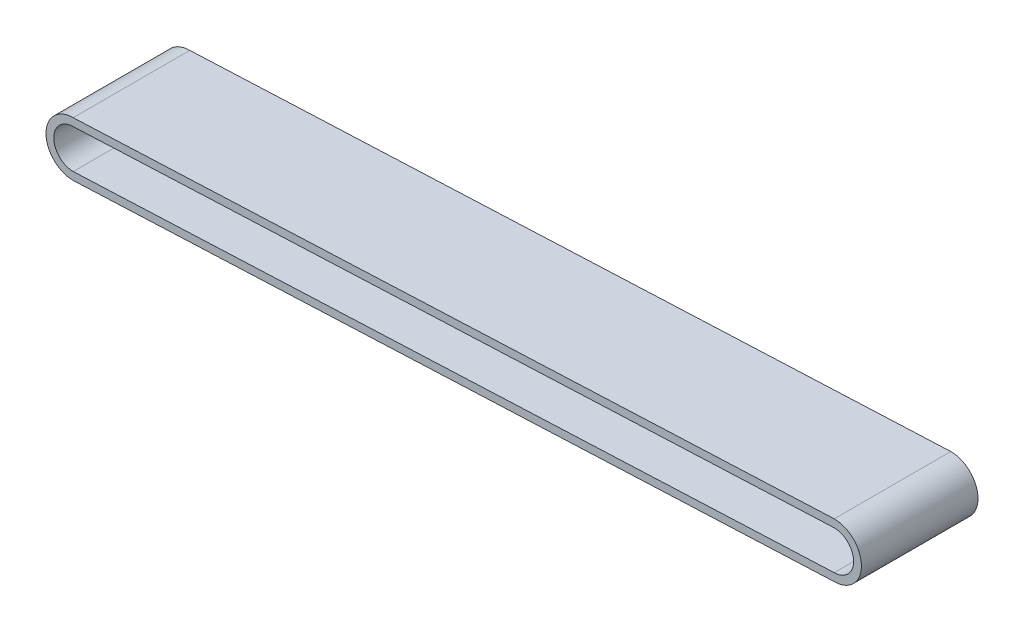
SolidWorks part; units mm, degrees
ref_plane "Front Plane" through (0, 0, 0) normal (0, 0, 1) x (1, 0, 0)
ref_plane "Top Plane" through (0, 0, 0) normal (0, 1, 0) x (1, 0, 0)
ref_plane "Right Plane" through (0, 0, 0) normal (1, 0, 0) x (0, 0, -1)
sketch "Sketch1" plane through (0, 0, 0) normal (0, 0, 1) x (1, 0, 0)
  line L1 (-230, -7.5) -> (259.5368, 13.8015)
  line L2 (-230, -32.5) -> (259.5368, -11.1985)
  line L3 (-207.5, -20) -> (-230, -20)
  line L4 (-230, -2.5) -> (259.5368, 18.8015)
  line L5 (-230, -37.5) -> (259.7542, -16.1972)
  arc A1 (-230, -7.5) -> (-230, -32.5) centre (-230, -20) ccw
  arc A2 (259.5368, -11.1985) -> (259.5368, 13.8015) centre (259.5368, 1.3015) ccw
  arc A3 (-230, -2.5) -> (-230, -37.5) centre (-230, -20) ccw
  arc A4 (259.7542, -16.1972) -> (259.5368, 18.8015) centre (259.5368, 1.3015) ccw
  point P4 (0, 0)
  dimension "D2" = 25
  dimension "D3" = 25
  dimension "D4" = 35
  dimension "D5" = 35
  dimension "D1" = 490
extrude "Boss-Extrude1" add sketch "Sketch1" along normal blind 75 contours L5 A4 L4 A3 A2 L2 A1 L1
